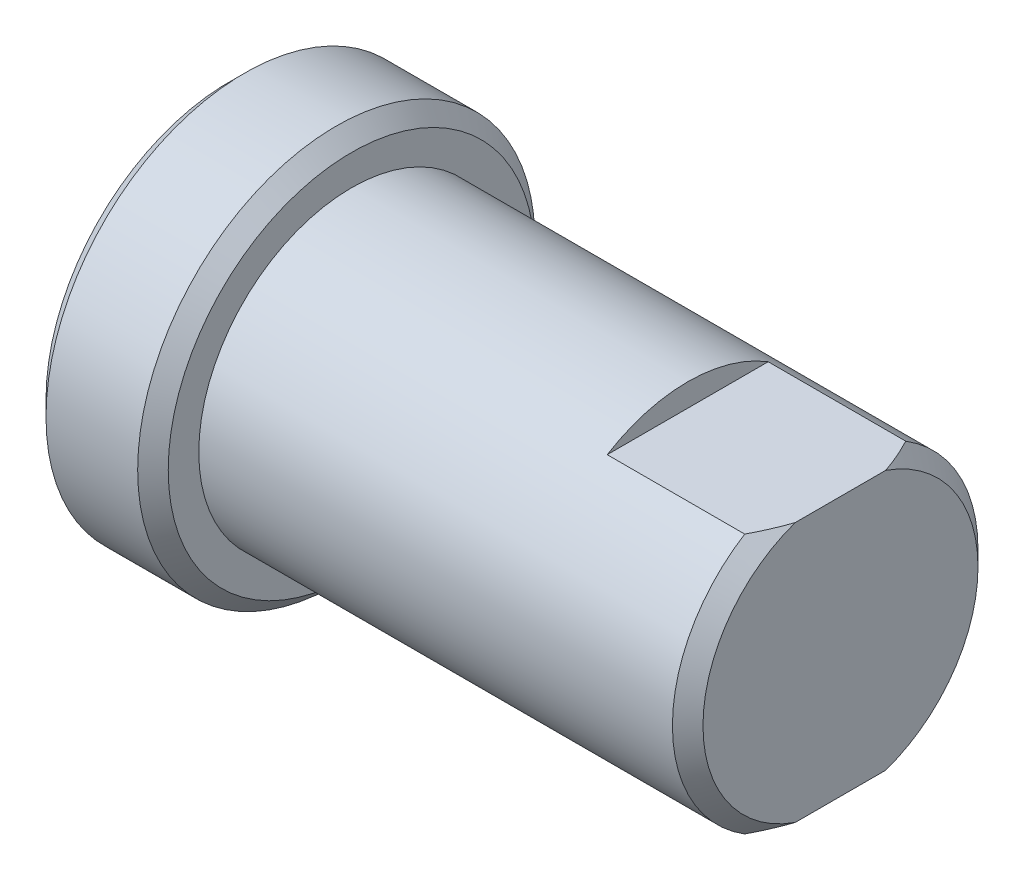
SolidWorks part; units mm, degrees
ref_plane "Front Plane" through (0, 0, 0) normal (0, 0, 1) x (1, 0, 0)
ref_plane "Top Plane" through (0, 0, 0) normal (0, 1, 0) x (1, 0, 0)
ref_plane "Right Plane" through (0, 0, 0) normal (1, 0, 0) x (0, 0, -1)
sketch "Sketch1" plane through (0, 0, 0) normal (0, 0, 1) x (1, 0, 0)
  line L0 (0, 0) -> (40, 0) construction
  line L1 (0, 0) -> (0, 13)
  line L2 (0, 13) -> (8, 13)
  line L3 (8, 13) -> (8, 10)
  line L4 (8, 10) -> (40, 10)
  line L5 (40, 10) -> (40, 0)
  line L6 (0, 0) -> (40, 0)
  dimension "D1" = 40
  dimension "D2" = 13
  dimension "D3" = 8
  dimension "D4" = 10
revolve "Revolve1" add sketch "Sketch1" angle 360 about L0
chamfer "Chamfer1" distance 1 angle 45 3 edges at (40, 0, 10) (8, 0, 13) (0, 0, 13)
sketch "Sketch2" plane through (40, 0, 0) normal (1, 0, 0) x (0, 0, -1)
  line L0 (-23.7398, 0) -> (23.7398, 0) construction
  line L1 (-23.7398, -8.5) -> (23.7398, -8.5)
  line L2 (-23.7398, 8.5) -> (23.7398, 8.5)
  circle A0 centre (0, 0) radius 10 construction
  circle A1 centre (0, 0) radius 10
  point P5 (0, 0)
  circle M4 centre (0, 0) radius 9
  dimension "D1" = 8.5
  dimension "D2" = 8.5
extrude "Cut-Extrude1" cut sketch "Sketch2" against normal blind 10 contours L2 A1 M4 | L2 M4 | L1 A1 M4 | L1 M4
